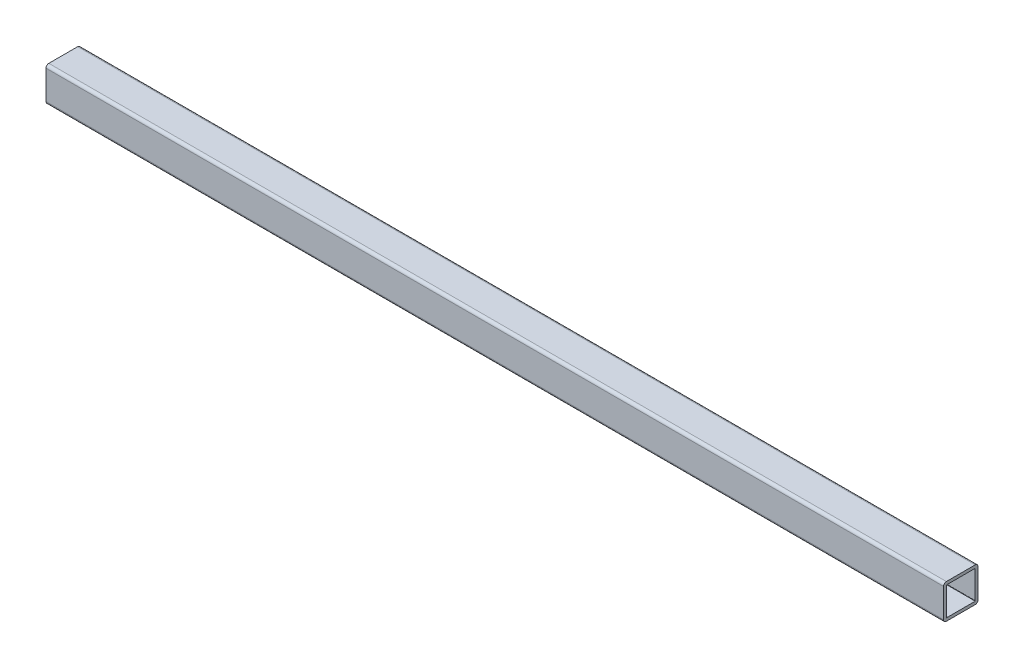
SolidWorks part; units mm, degrees
material "Plain Carbon Steel"
ref_plane "Front Plane" through (0, 0, 0) normal (0, 0, 1) x (1, 0, 0)
ref_plane "Top Plane" through (0, 0, 0) normal (0, 1, 0) x (1, 0, 0)
ref_plane "Right Plane" through (0, 0, 0) normal (1, 0, 0) x (0, 0, -1)
sketch "Sketch1" plane through (0, 0, 0) normal (1, 0, 0) x (0, 0, -1)
  line L0 (-0.1864, 2.5839) -> (-0.1864, 29.1661)
  line L1 (-2.7702, 31.75) -> (-29.3525, 31.75)
  line L2 (-31.9364, 29.1661) -> (-31.9364, 2.5839)
  line L3 (-29.3525, 0) -> (-2.7702, 0)
  line L12 (-2.938, 3.3888) -> (-2.938, 28.9566)
  line L13 (-2.7279, 28.9983) -> (-28.2957, 28.9983)
  line L14 (-29.1847, 28.1093) -> (-29.1847, 2.5415)
  line L15 (-28.2957, 2.7517) -> (-2.7279, 2.7517)
  arc A0 (-31.9364, 2.5839) -> (-29.3525, 0) centre (-29.3525, 2.5839) ccw
  arc A1 (-0.1864, 2.5839) -> (-2.7702, 0) centre (-2.7702, 2.5839) cw
  arc A2 (-0.1864, 29.1661) -> (-2.7702, 31.75) centre (-2.7702, 29.1661) ccw
  arc A3 (-31.9364, 29.1661) -> (-29.3525, 31.75) centre (-29.3525, 29.1661) cw
  arc A16 (-2.938, 3.3888) -> (-2.7279, 2.7517) centre (-3.6148, 2.8124) cw
  arc A17 (-28.2957, 2.7517) -> (-29.1847, 2.5415) centre (-28.9156, 3.3888) cw
  arc A18 (-2.938, 28.9566) -> (-2.7279, 28.9983) centre (-3.0047, 29.8431) ccw
  arc A19 (-29.1847, 28.1093) -> (-28.2957, 28.9983) centre (-28.2957, 28.1093) cw
  point P12 (0, 0)
  point P15 (0, 31.6215)
  point P18 (-31.75, 31.6215)
  point P23 (-29.1847, 1.651)
  dimension "D7" = 2.5839
  dimension "D8" = 0.889
  dimension "D1" = 2.7517
  dimension "D2" = 2.7517
  dimension "D3" = 2.7517
  dimension "D4" = 2.7517
  dimension "D5" = 31.75
  dimension "D6" = 31.75
  dimension "D21" = 31.75
  dimension "D9" = 0.1864
  dimension "D10" = 2.7279
  dimension "D11" = 1.651
  dimension "D12" = 31.6215
extrude "Boss-Extrude1" add sketch "Sketch1" along normal blind 609.6
scale "Scale1" bodies to scale 101 scale about centroid uniform scaling no x scale factor 1 y scale factor 0.6 z scale factor 0.6
sketch "Sketch2" plane through (0, 25.4072, 0) normal (0, 1, 0) x (1, 0, 0)
  line L0 (0, -8.0884) -> (0, -24.0377) construction
  line L1 (609.6, -24.0377) -> (0, -24.0377) construction
  circle A0 centre (50.9509, -19.2381) radius 3.175
  circle A1 centre (63.3491, -19.2381) radius 3.175
  dimension "D1" = 6.35
  dimension "D2" = 50.9509
  dimension "D3" = 63.3491
  dimension "D4" = 4.7997
extrude "Cut-Extrude1" [suppressed] cut sketch "Sketch2" against normal blind 2.54
sketch "Sketch3" plane through (0, 0, 25.5881) normal (0, 0, 1) x (1, 0, 0)
  line L0 (609.6, 25.4072) -> (0, 25.4072) construction
  line L1 (496.0595, 25.4072) -> (609.6, 25.4072)
  line L2 (496.0595, 25.4072) -> (496.0595, 6.3572)
  line L3 (496.0595, 6.3572) -> (609.6, 6.3572)
  line L4 (609.6, 25.4072) -> (609.6, 6.3572)
  line L5 (552.8297, 6.3572) -> (552.8297, 25.4072) construction
  line L6 (496.0595, 15.8822) -> (609.6, 15.8822) construction
  point P6 (0, 0)
  point P7 (496.0595, 25.4072)
  point P176 (552.8297, 15.8822)
extrude "Cut-Extrude2" cut sketch "Sketch3" against normal through all
equation "\"BeamTickness\"= 0.065in / 0.6"
equation "\"D1@Sketch1\"=\"BeamTickness\""
equation "\"D2@Sketch1\"=\"BeamTickness\""
equation "\"D3@Sketch1\"=\"BeamTickness\""
equation "\"D4@Sketch1\"=\"BeamTickness\""
